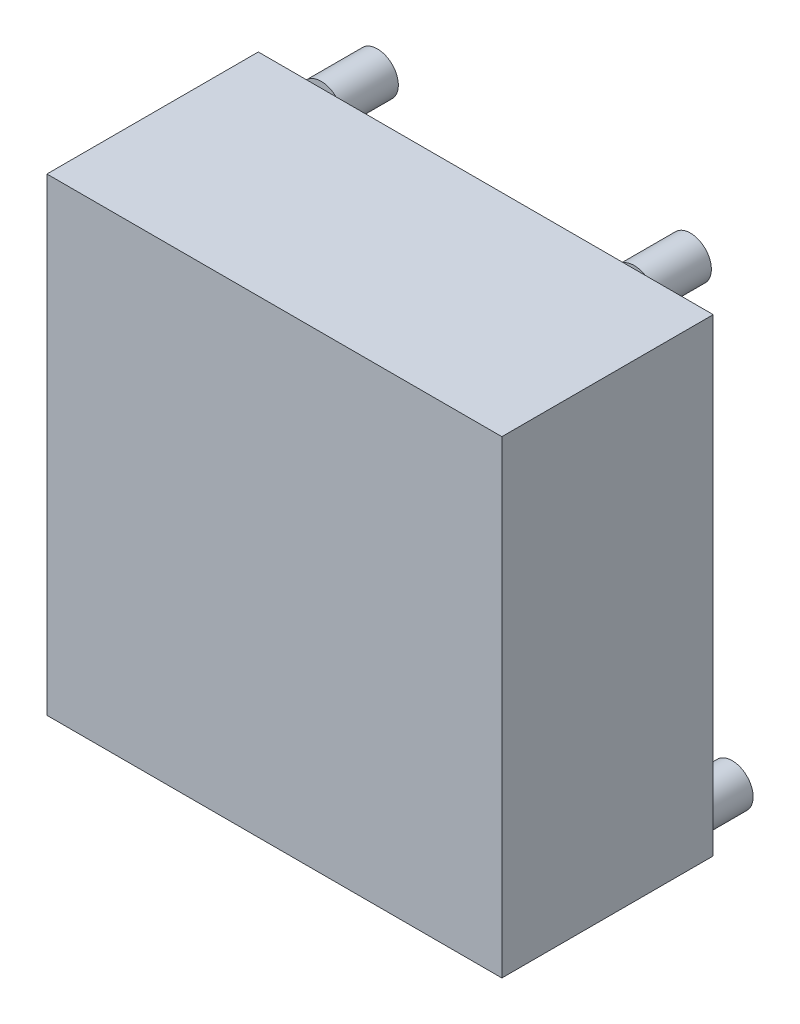
SolidWorks part; units mm, degrees
ref_plane "Front Plane" through (0, 0, 0) normal (0, 0, 1) x (1, 0, 0)
ref_plane "Top Plane" through (0, 0, 0) normal (0, 1, 0) x (1, 0, 0)
ref_plane "Right Plane" through (0, 0, 0) normal (1, 0, 0) x (0, 0, -1)
sketch "Sketch1" plane through (0, 0, 0) normal (0, 0, 1) x (1, 0, 0)
  line L1 (0, 0) -> (77.5208, 0)
  line L2 (0, 0) -> (0, 79.883)
  line L3 (0, 79.883) -> (77.5208, 79.883)
  line L4 (77.5208, 0) -> (77.5208, 79.883)
  dimension "D1" = 79.883
  dimension "D2" = 77.5208
extrude "Boss-Extrude1" add sketch "Sketch1" along normal blind 36.0172
sketch "Sketch3" plane through (0, 0, 36.0172) normal (0, 0, 1) x (1, 0, 0)
  line L1 (0, 0) -> (8.6811, 0)
  line L2 (0, 0) -> (0, 9.3476)
  line L3 (0, 9.3476) -> (8.6811, 9.3476)
  line L4 (8.6811, 0) -> (8.6811, 9.3476)
  text T0 "09"
sketch "Sketch4" plane through (0, 0, 0) normal (0, 0, -1) x (-1, 0, 0)
  line L0 (-77.5208, 2.54) -> (-71.1708, 2.54) construction
  line L1 (-77.5208, 0) -> (-77.5208, 79.883) construction
  line L2 (-71.1708, 2.54) -> (-71.1708, 0) construction
  line L3 (0, 0) -> (-77.5208, 0) construction
  line L4 (0, 2.4525) -> (-3.0734, 2.4525) construction
  line L5 (0, 79.883) -> (0, 0) construction
  line L7 (-5.1989, 2.54) -> (-5.1989, 0) construction
  circle A0 centre (-71.1708, 2.54) radius 3.5687
  circle A1 centre (-3.0734, 2.4525) radius 3.5687
  dimension "D3" = 7.1374
  dimension "D6" = 7.1374
  dimension "D1" = 2.54
  dimension "D2" = 6.35
  dimension "D4" = 2.54
  dimension "D5" = 3.0734
extrude "Boss-Extrude2" add sketch "Sketch4" along normal blind 9.5758
sketch "Sketch5" plane through (0, 0, 0) normal (0, 0, -1) x (-1, 0, 0)
  line L0 (-10.7188, 79.883) -> (-10.7188, 77.343) construction
  line L1 (-77.5208, 79.883) -> (0, 79.883) construction
  line L2 (-10.7188, 77.343) -> (0, 77.343) construction
  line L3 (0, 79.883) -> (0, 4.2663) construction
  line L4 (-77.5208, 76.835) -> (-64.0588, 76.835) construction
  line L5 (-77.5208, 0) -> (-77.5208, 79.883) construction
  line L6 (-64.0588, 76.835) -> (-64.0588, 79.883) construction
  circle A0 centre (-10.7188, 77.343) radius 3.5687
  circle A1 centre (-64.0588, 76.835) radius 3.5687
  dimension "D3" = 7.1374
  dimension "D6" = 7.1374
  dimension "D1" = 2.54
  dimension "D2" = 10.7188
  dimension "D4" = 3.048
  dimension "D5" = 13.462
extrude "Boss-Extrude3" add sketch "Sketch5" along normal blind 9.5758
sketch "Sketch6" plane through (0, 0, -9.5758) normal (0, 0, -1) x (-1, 0, 0)
  circle A1 centre (-71.1708, 2.54) radius 1.3462
  circle A2 centre (-3.0734, 2.4525) radius 1.3462
  circle A3 centre (-10.7188, 77.343) radius 1.3462
  circle A4 centre (-64.0588, 76.835) radius 1.3462
  dimension "D1" = 2.6924
  dimension "D2" = 2.6924
  dimension "D3" = 2.6924
  dimension "D4" = 2.6924
extrude "Cut-Extrude1" cut sketch "Sketch6" against normal blind 8.636
